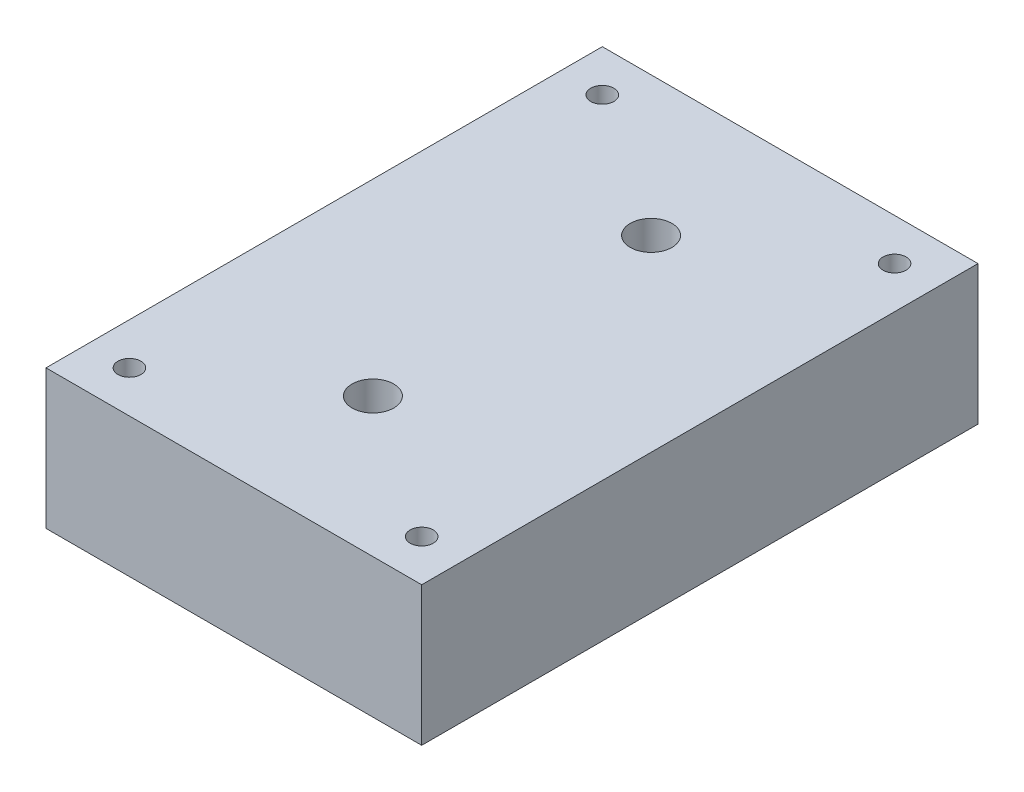
SolidWorks part; units mm, degrees
ref_plane "Ebene vorne" through (0, 0, 0) normal (0, 0, 1) x (1, 0, 0)
ref_plane "Ebene oben" through (0, 0, 0) normal (0, 1, 0) x (1, 0, 0)
ref_plane "Ebene rechts" through (0, 0, 0) normal (1, 0, 0) x (0, 0, -1)
sketch "Skizze1" plane through (0, 0, 0) normal (0, 0, 1) x (1, 0, 0)
  line L1 (67.5347, -25) -> (-67.5347, -25)
  line L2 (67.5347, -25) -> (67.5347, 25)
  line L3 (67.5347, 25) -> (-67.5347, 25)
  line L4 (-67.5347, -25) -> (-67.5347, 25)
  line L5 (67.5347, -25) -> (-67.5347, 25) construction
  line L6 (67.5347, 25) -> (-67.5347, -25) construction
  point P0 (0, 0)
  dimension "D1" = 50
  dimension "D2" = 135.0694
extrude "Aufsatz-Linear austragen1" add sketch "Skizze1" along normal blind 200 contours L4 L3 L2 L1
ref_plane "Ebene1" through (0, 0, 100) normal (0, 0, 1) x (1, 0, 0)
sketch "Skizze3" plane through (0, 25, 0) normal (0, 1, 0) x (1, 0, 0)
  line L0 (-67.5347, -200) -> (-67.5347, 0) construction
  line L1 (67.5347, -200) -> (67.5347, 0) construction
  line L2 (-27.5, -100) -> (27.5, -100) construction
  circle A0 centre (0, -150) radius 67.5347
  dimension "D1" = 50
hole_wizard "Stirnsenkung für M8 Senkschraube (Kopf Button)1" positions "Skizze5" profile "Skizze4" counterbore size "M8" standard "ANSI Metrisch" end condition through all
sketch "Skizze5" plane through (0, 25, 0) normal (0, 1, 0) x (1, 0, 0)
  point P0 (0, -150)
sketch "Skizze4" plane through (0, 25, 150) normal (1, 0, 0) x (0, 0, 1)
  line L0 (0, 0) -> (0, 50)
  line L1 (0, 50) -> (4.5, 50)
  line L3 (4.5, 50) -> (4.5, 34.5)
  line L4 (4.5, 34.5) -> (7.5, 34.5)
  line L5 (7.5, 34.5) -> (7.5, 0)
  line L7 (7.5, 0) -> (0, 0)
  line L11 (0, -6.35) -> (0, 107.95) construction
  dimension "Bohrerdurchmesser" = 9
  dimension "Bohrungstiefe" = 50
  dimension "Senkdurchmesser2" = 15
  dimension "Senktiefe2" = 34.5
hole_wizard "Stirnsenkung für M8 Senkschraube (Kopf Button)2" positions "Skizze7" profile "Skizze6" counterbore size "M8" standard "ANSI Metrisch" end condition up to next
sketch "Skizze7" plane through (0, -25, 0) normal (0, -1, 0) x (-1, 0, 0)
  point P0 (0, -150)
sketch "Skizze6" plane through (0, -25, 150) normal (1, 0, 0) x (0, 0, -1)
  line L0 (0, 0) -> (0, 50)
  line L1 (0, 50) -> (4.5, 50)
  line L3 (4.5, 50) -> (4.5, 6.5)
  line L4 (4.5, 6.5) -> (7.5, 6.5)
  line L5 (7.5, 6.5) -> (7.5, 0)
  line L7 (7.5, 0) -> (0, 0)
  line L11 (0, -6.35) -> (0, 107.95) construction
  dimension "Bohrerdurchmesser" = 9
  dimension "Bohrungstiefe" = 50
  dimension "Senkdurchmesser2" = 15
  dimension "Senktiefe2" = 6.5
mirror "Spiegeln1" about plane through (0, 0, 100) normal (0, 0, 1) of "Stirnsenkung für M8 Senkschraube (Kopf Button)1", "Stirnsenkung für M8 Senkschraube (Kopf Button)2"
hole_wizard "Kernloch für M8 Helicoil1" positions "Skizze9" profile "Skizze10" hole size "M8x1.25" standard "ANSI Metrisch"
sketch "Skizze9" plane through (0, 25, 0) normal (0, 1, 0) x (1, 0, 0)
  line L1 (67.5347, -200) -> (-67.5347, -200) construction
  line L2 (-67.5347, -200) -> (-67.5347, 0) construction
  circle A0 centre (-52.5347, -185) radius 15
  point P1 (-52.5347, -185)
  dimension "D1" = 30
sketch "Skizze10" plane through (-52.5347, 25, 185) normal (1, 0, 0) x (0, 0, 1)
  line L0 (0, 0) -> (0, 32.4936)
  line L1 (0, 32.4936) -> (4.15, 30)
  line L2 (4.15, 30) -> (4.15, 0)
  line L5 (4.15, 0) -> (0, 0)
  line L10 (0, 32.4936) -> (-4.15, 30) construction
  line L11 (0, -6.35) -> (0, 107.95) construction
  dimension "Bohrerdurchmesser" = 8.3
  dimension "Bohrungstiefe" = 30
  dimension "Spitzenwinkel" = 118
mirror "Spiegeln2" about plane through (0, 0, 0) normal (1, 0, 0) of "Kernloch für M8 Helicoil1"
mirror "Spiegeln3" about plane through (0, 0, 100) normal (0, 0, 1) of "Spiegeln2", "Kernloch für M8 Helicoil1"
